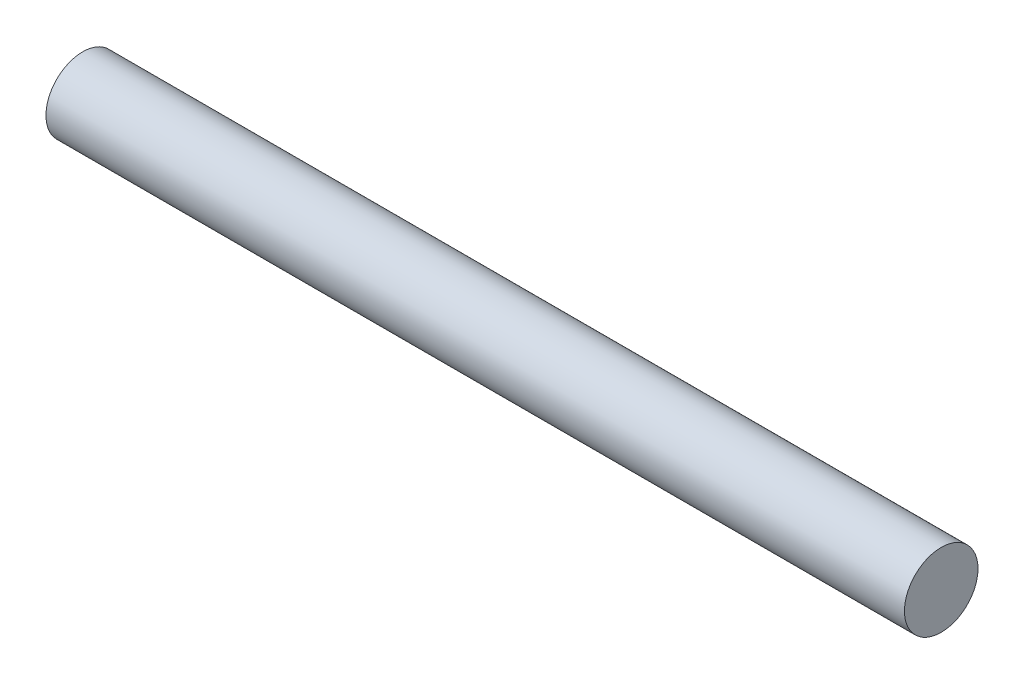
SolidWorks part; units mm, degrees
ref_plane "Front Plane" through (0, 0, 0) normal (0, 0, 1) x (1, 0, 0)
ref_plane "Top Plane" through (0, 0, 0) normal (0, 1, 0) x (1, 0, 0)
ref_plane "Right Plane" through (0, 0, 0) normal (1, 0, 0) x (0, 0, -1)
sketch "Sketch1" plane through (0, 0, 0) normal (1, 0, 0) x (0, 0, -1)
  circle A0 centre (0, 0) radius 1.5
  dimension "D1" = 3
extrude "Boss-Extrude1" add sketch "Sketch1" along normal blind 35
